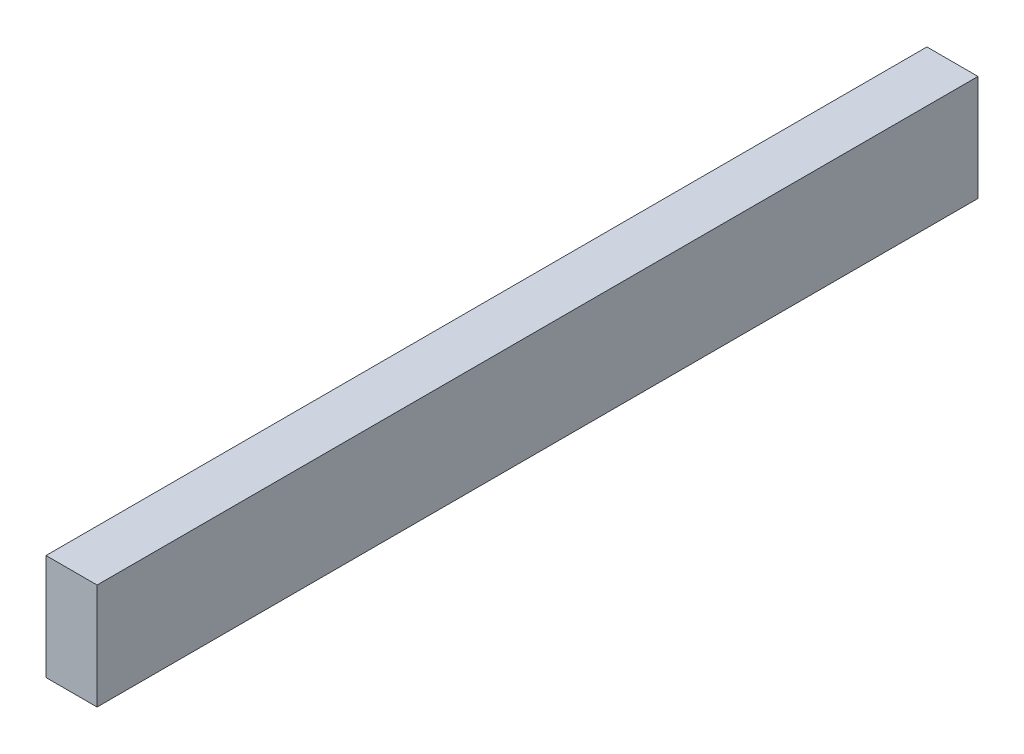
SolidWorks part; units mm, degrees
ref_plane "Front Plane" through (0, 0, 0) normal (0, 0, 1) x (1, 0, 0)
ref_plane "Top Plane" through (0, 0, 0) normal (0, 1, 0) x (1, 0, 0)
ref_plane "Right Plane" through (0, 0, 0) normal (1, 0, 0) x (0, 0, -1)
sketch "Sketch1" plane through (0, 0, 0) normal (0, 0, 1) x (1, 0, 0)
  line L1 (0, 0) -> (29, 0)
  line L2 (0, 0) -> (0, 60)
  line L3 (0, 60) -> (29, 60)
  line L4 (29, 0) -> (29, 60)
  dimension "D1" = 29
  dimension "D2" = 60
extrude "Boss-Extrude1" add sketch "Sketch1" along normal blind 500
